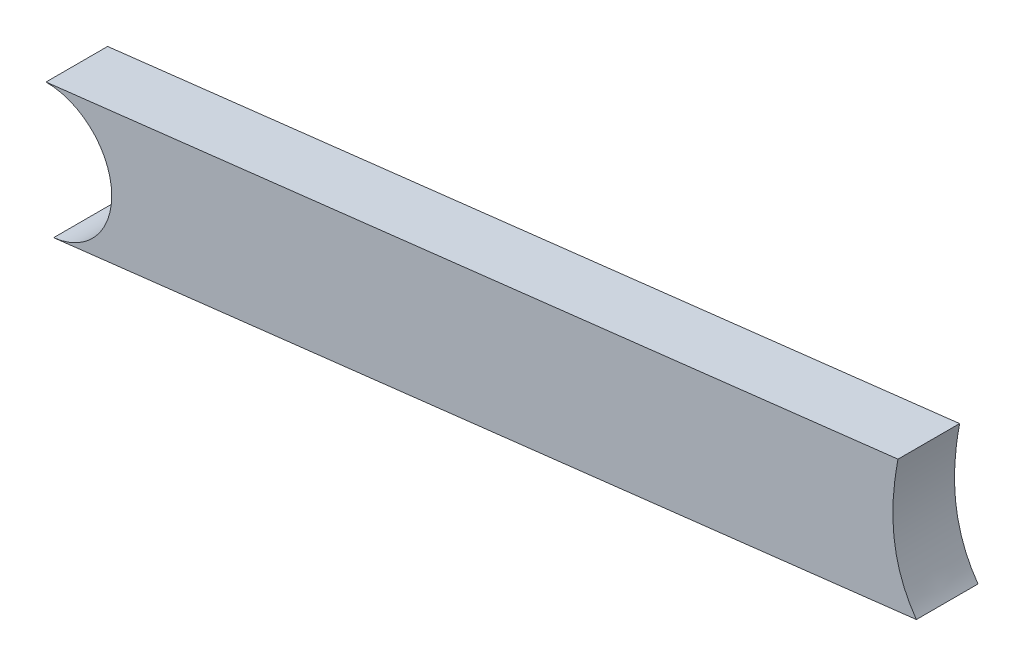
SolidWorks part; units mm, degrees
material "Titanium"
ref_plane "Front Plane" through (0, 0, 0) normal (0, 0, 1) x (1, 0, 0)
ref_plane "Top Plane" through (0, 0, 0) normal (0, 1, 0) x (1, 0, 0)
ref_plane "Right Plane" through (0, 0, 0) normal (1, 0, 0) x (0, 0, -1)
sketch "Sketch1" plane through (0, 0, 0) normal (0, 0, 1) x (1, 0, 0)
  line L0 (0, 50.4744) -> (41.4837, 55.3138)
  line L1 (0.3708, 44.096) -> (42.3791, 48.9965)
  circle A0 centre (0, 47.2744) radius 3.2 construction
  arc A1 (0.3708, 44.096) -> (0, 50.4744) centre (0, 47.2744) ccw
  spline S0 degree 3 poles (42.3791, 48.9965) (40.8598, 51.1124) (41.1894, 53.7107) (41.4837, 55.3138) knots 0 0 0 0 1 1 1 1
extrude "Boss-Extrude1" add sketch "Sketch1" against normal blind 3
